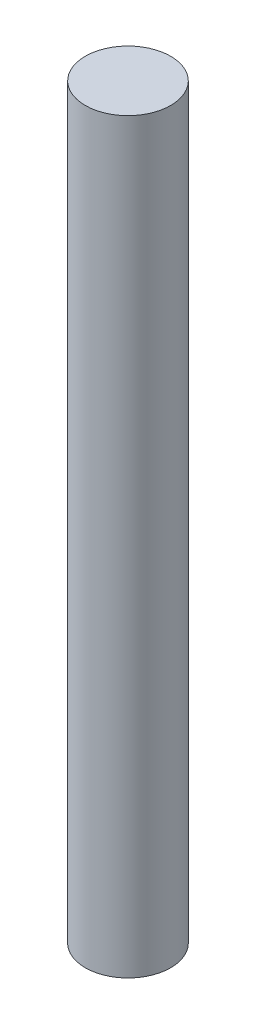
SolidWorks part; units mm, degrees
ref_plane "Front Plane" through (0, 0, 0) normal (0, 0, 1) x (1, 0, 0)
ref_plane "Top Plane" through (0, 0, 0) normal (0, 1, 0) x (1, 0, 0)
ref_plane "Right Plane" through (0, 0, 0) normal (1, 0, 0) x (0, 0, -1)
sketch "Sketch1" plane through (0, 0, 0) normal (0, 1, 0) x (1, 0, 0)
  circle A0 centre (0, 0) radius 4
  dimension "D1" = 8
extrude "Boss-Extrude2" add sketch "Sketch1" along normal blind 70
